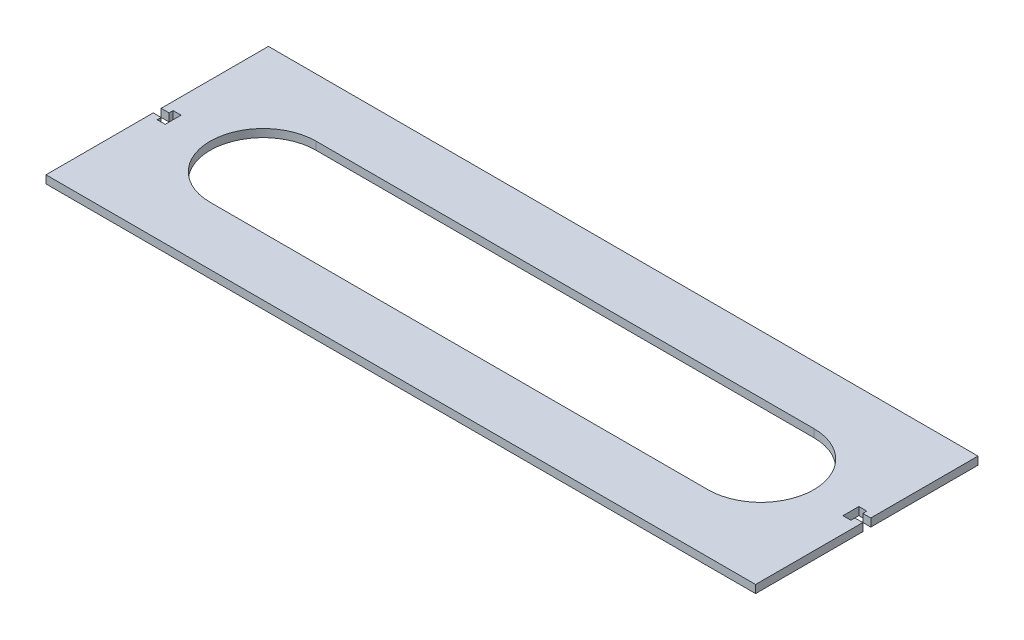
SolidWorks part; units mm, degrees
ref_plane "Alzado" through (0, 0, 0) normal (0, 0, 1) x (1, 0, 0)
ref_plane "Planta" through (0, 0, 0) normal (0, 1, 0) x (1, 0, 0)
ref_plane "Vista lateral" through (0, 0, 0) normal (1, 0, 0) x (0, 0, -1)
sketch "Croquis1" plane through (0, 0, 0) normal (0, 1, 0) x (1, 0, 0)
  line L0 (94, 0) -> (-94, 0) construction
  line L1 (134, -42) -> (-134, -42)
  line L2 (134, -42) -> (134, -1.5)
  line L3 (134, 42) -> (-134, 42)
  line L4 (-134, -42) -> (-134, -1.5)
  line L5 (134, -42) -> (-134, 42) construction
  line L6 (134, 42) -> (-134, -42) construction
  line L7 (94, -20) -> (-94, -20)
  line L8 (94, 20) -> (-94, 20)
  line L9 (-134, 0) -> (-128, 0) construction
  line L10 (-134, 1.5) -> (-131, 1.5)
  line L11 (-131, 1.5) -> (-131, 3)
  line L12 (-131, 3) -> (-128, 3)
  line L13 (-128, 3) -> (-128, -3)
  line L14 (-131, -1.5) -> (-131, -3)
  line L15 (-131, -3) -> (-128, -3)
  line L16 (-134, -1.5) -> (-131, -1.5)
  line L17 (-134, 1.5) -> (-134, 42)
  line L18 (0, 0) -> (0, 42) construction
  line L19 (134, 1.5) -> (131, 1.5)
  line L20 (131, 1.5) -> (131, 3)
  line L21 (131, 3) -> (128, 3)
  line L22 (128, 3) -> (128, -3)
  line L23 (131, -3) -> (128, -3)
  line L24 (131, -1.5) -> (131, -3)
  line L25 (134, -1.5) -> (131, -1.5)
  line L26 (134, 1.5) -> (134, 42)
  arc A0 (94, -20) -> (94, 20) centre (94, 0) ccw
  arc A1 (-94, 20) -> (-94, -20) centre (-94, 0) ccw
  point P0 (0, 0)
  point P8 (0, 0)
  point P14 (-114, 0)
  dimension "D4" = 20
  dimension "D1" = 268
  dimension "D2" = 84
  dimension "D3" = 40
  dimension "D5" = 6
  dimension "D6" = 1.5
  dimension "D7" = 3
  dimension "D8" = 3
extrude "Saliente-Extruir2" add sketch "Croquis1" along normal blind 3
